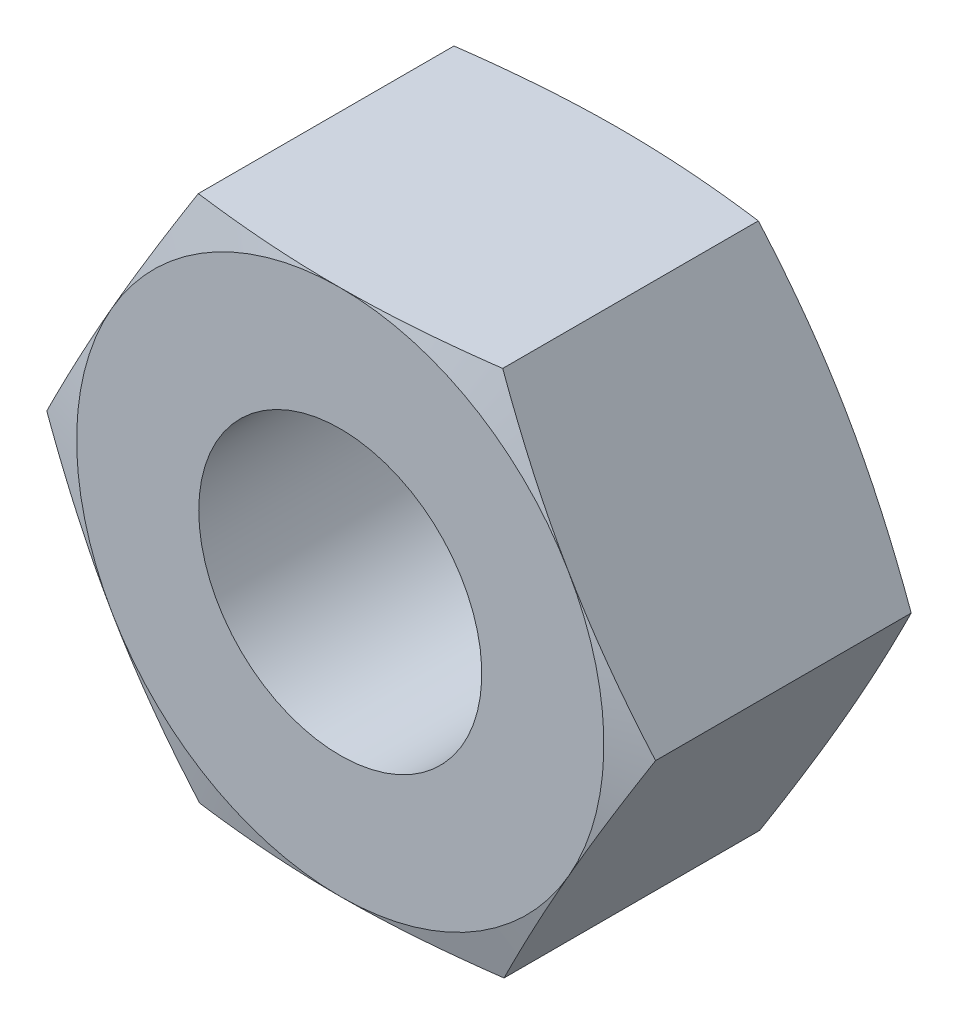
SolidWorks part; units mm, degrees
ref_plane "Plano frontal" through (0, 0, 0) normal (0, 0, 1) x (1, 0, 0)
ref_plane "Plano superior" through (0, 0, 0) normal (0, 1, 0) x (1, 0, 0)
ref_plane "Plano direito" through (0, 0, 0) normal (1, 0, 0) x (0, 0, -1)
sketch "Esboço1" plane through (0, 0, 0) normal (0, 0, 1) x (1, 0, 0)
  line L1 (5.4604, 9.514) -> (-5.5092, 9.4859)
  line L2 (-5.5092, 9.4859) -> (-10.9696, -0.0281)
  line L3 (-10.9696, -0.0281) -> (-5.4604, -9.514)
  line L4 (-5.4604, -9.514) -> (5.5092, -9.4859)
  line L5 (5.5092, -9.4859) -> (10.9696, 0.0281)
  line L6 (10.9696, 0.0281) -> (5.4604, 9.514)
  circle A0 centre (0, 0) radius 9.5 construction
  dimension "D1" = 19
extrude "Ressalto-extrusão1" add sketch "Esboço1" along normal blind 10
sketch "Esboço2" plane through (0, 0, 10) normal (0, 0, 1) x (1, 0, 0)
  circle A0 centre (0, 0) radius 9.5
extrude "Corte-extrusão1" cut sketch "Esboço2" against normal blind 15 draft 75 flip side to cut
sketch "Esboço3" plane through (0, 0, 0) normal (0, 0, -1) x (-1, 0, 0)
  circle A0 centre (0, 0) radius 9.5
extrude "Corte-extrusão2" cut sketch "Esboço3" against normal blind 15 draft 75 flip side to cut
hole_wizard "Furo roscado de M121" positions "Esboço4" profile "Esboço5" tap size "M12" standard "DIN" end condition through all
sketch "Esboço4" plane through (0, 0, 0) normal (0, 0, -1) x (-1, 0, 0)
  point P0 (0, 0)
sketch "Esboço5" plane through (0, 0, 0) normal (1, 0, 0) x (0, 1, 0)
  line L0 (0, 0) -> (0, 10)
  line L1 (0, 10) -> (5.1, 10)
  line L2 (5.1, 10) -> (5.1, 0)
  line L5 (5.1, 0) -> (0, 0)
  line L11 (0, -6.35) -> (0, 107.95) construction
  dimension "Thru Tap Drill Dia." = 10.2
  dimension "Thru Tap Drill Depth" = 10
cosmetic thread "Rosca de furo1" parameters "D2"=12
